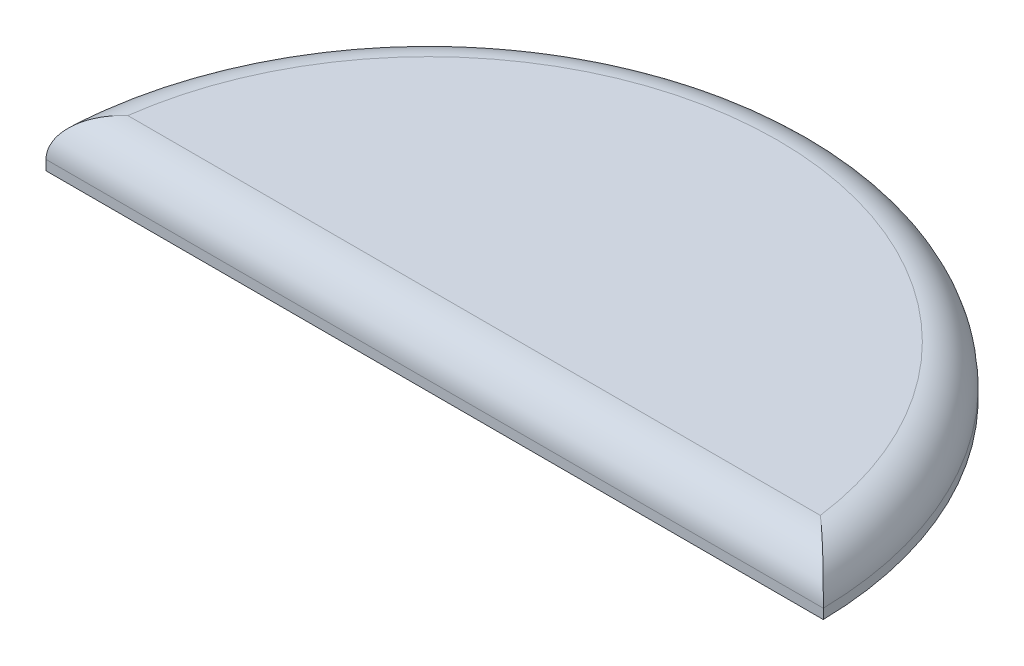
SolidWorks part; units mm, degrees
ref_plane "Front Plane" through (0, 0, 0) normal (0, 0, 1) x (1, 0, 0)
ref_plane "Top Plane" through (0, 0, 0) normal (0, 1, 0) x (1, 0, 0)
ref_plane "Right Plane" through (0, 0, 0) normal (1, 0, 0) x (0, 0, -1)
sketch "Sketch1" plane through (0, 0, 0) normal (0, 1, 0) x (1, 0, 0)
  line L0 (-41.9855, 0) -> (36.8445, 0)
  arc A0 (-41.9855, 0) -> (36.8445, 0) centre (-2.5705, -0.6278) cw
  dimension "D2" = 39.42
  dimension "D1" = 78.83
extrude "Boss-Extrude1" add sketch "Sketch1" along normal blind 5
fillet "Fillet1" radius 4 2 edges at (-2.5705, 5, 0) (-2.5705, 5, -38.7922)
